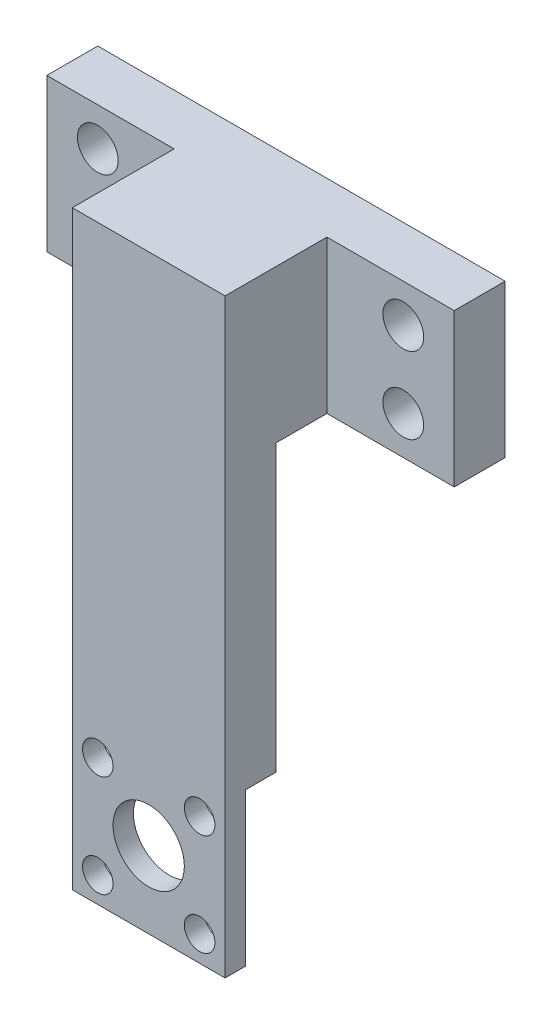
SolidWorks part; units mm, degrees
ref_plane "Front Plane" through (0, 0, 0) normal (0, 0, 1) x (1, 0, 0)
ref_plane "Top Plane" through (0, 0, 0) normal (0, 1, 0) x (1, 0, 0)
ref_plane "Right Plane" through (0, 0, 0) normal (1, 0, 0) x (0, 0, -1)
sketch "Sketch2" plane through (0, 0, 0) normal (0, 0, 1) x (1, 0, 0)
  line L0 (0, 7.5) -> (40, 7.5) construction
  line L1 (0, 0) -> (40, 0)
  line L2 (0, 0) -> (0, 15)
  line L3 (0, 15) -> (40, 15)
  line L4 (40, 0) -> (40, 15)
  line L5 (20, 15) -> (20, 0) construction
  circle A0 centre (5, 3.75) radius 2
  circle A1 centre (5, 11.25) radius 2
  circle A2 centre (35, 3.75) radius 2
  circle A3 centre (35, 11.25) radius 2
  dimension "D3" = 4
  dimension "D1" = 15
  dimension "D2" = 40
  dimension "D4" = 5
  dimension "D5" = 3.75
extrude "Boss-Extrude1" add sketch "Sketch2" along normal blind 5
sketch "Sketch3" plane through (0, 0, 5) normal (0, 0, 1) x (1, 0, 0)
  line L0 (40, 15) -> (0, 15) construction
  line L1 (12.5, 15) -> (27.5, 15)
  line L2 (12.5, 15) -> (12.5, 0)
  line L3 (12.5, 0) -> (27.5, 0)
  line L4 (27.5, 15) -> (27.5, 0)
  line L5 (0, 0) -> (40, 0) construction
  line L6 (0, 7.5) -> (40, 7.5) construction
  line L7 (0, 15) -> (0, 0) construction
  line L8 (40, 0) -> (40, 15) construction
  point P14 (20, 7.5)
  point P15 (20, 15)
extrude "Boss-Extrude2" add sketch "Sketch3" along normal blind 10
sketch "Sketch4" plane through (0, 0, 0) normal (0, -1, 0) x (1, 0, 0)
  line L1 (12.5, 15) -> (27.5, 15)
  line L2 (12.5, 15) -> (12.5, 10)
  line L3 (12.5, 10) -> (27.5, 10)
  line L4 (27.5, 15) -> (27.5, 10)
  dimension "D1" = 5
  dimension "D2" = 15
extrude "Boss-Extrude3" add sketch "Sketch4" along normal blind 28
sketch "Sketch5" plane through (0, -28, 0) normal (0, -1, 0) x (1, 0, 0)
  line L1 (12.5, 15) -> (27.5, 15)
  line L2 (12.5, 15) -> (12.5, 13)
  line L3 (12.5, 13) -> (27.5, 13)
  line L4 (27.5, 15) -> (27.5, 13)
  dimension "D1" = 2
  dimension "D2" = 15
extrude "Boss-Extrude4" add sketch "Sketch5" along normal blind 15
sketch "Sketch6" plane through (0, 0, 13) normal (0, 0, -1) x (-1, 0, 0)
  line L0 (-12.5, -43) -> (-27.5, -43) construction
  line L1 (-25, -40.5) -> (-15, -40.5) construction
  line L2 (-25, -40.5) -> (-25, -30.5) construction
  line L3 (-25, -30.5) -> (-15, -30.5) construction
  line L4 (-15, -40.5) -> (-15, -30.5) construction
  line L5 (-25, -40.5) -> (-15, -30.5) construction
  line L6 (-25, -30.5) -> (-15, -40.5) construction
  line L7 (-12.5, -43) -> (-12.5, -28) construction
  circle A0 centre (-15, -30.5) radius 1.5
  circle A1 centre (-25, -30.5) radius 1.5
  circle A2 centre (-20, -35.5) radius 3.5
  circle A3 centre (-15, -40.5) radius 1.5
  circle A4 centre (-25, -40.5) radius 1.5
  point P4 (-20, -35.5)
  point P7 (-20, -43)
  point P10 (-12.5, -35.5)
  dimension "D2" = 3
  dimension "D3" = 3
  dimension "D4" = 7
  dimension "D5" = 3
  dimension "D6" = 3
  dimension "D1" = 10
extrude "Cut-Extrude1" cut sketch "Sketch6" against normal blind 15
